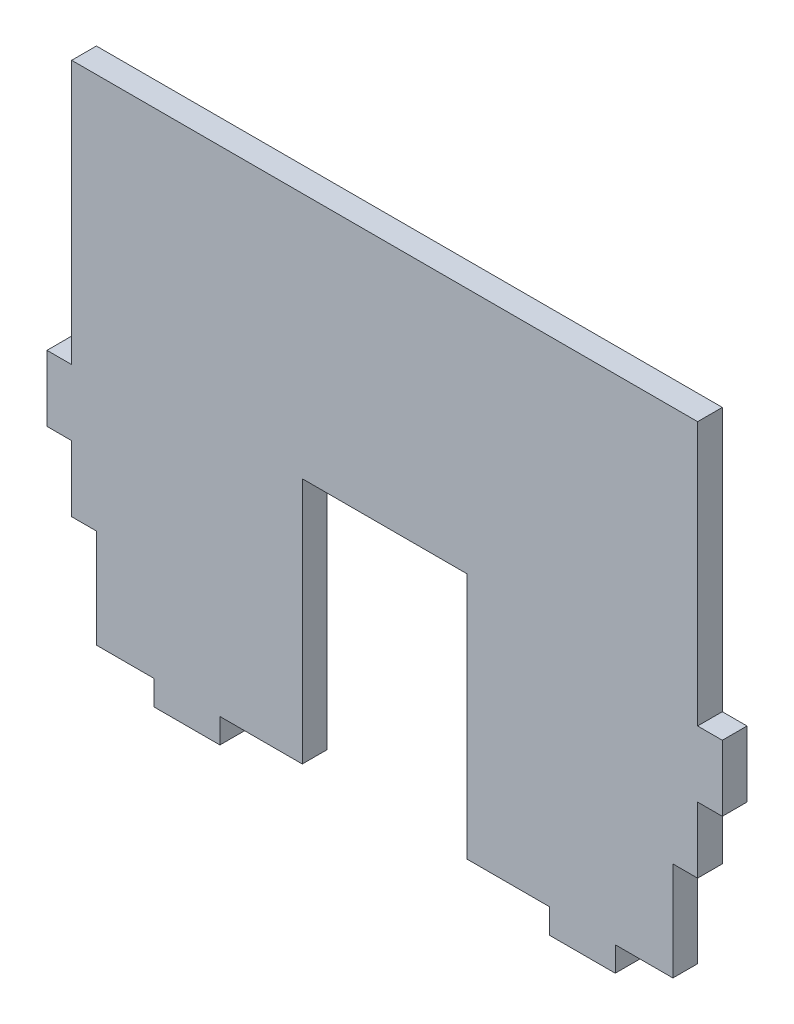
SolidWorks part; units mm, degrees
ref_plane "前视" through (0, 0, 0) normal (0, 0, 1) x (1, 0, 0)
ref_plane "上视" through (0, 0, 0) normal (0, 1, 0) x (1, 0, 0)
ref_plane "右视" through (0, 0, 0) normal (1, 0, 0) x (0, 0, -1)
sketch "草图1" plane through (0, 0, 0) normal (0, 0, 1) x (1, 0, 0)
  line L0 (10, 0) -> (10, -3)
  line L1 (3, 0) -> (10, 0)
  line L2 (0, 12) -> (0, 20)
  line L3 (0, 60) -> (76, 60)
  line L4 (0, 28) -> (-3, 28)
  line L5 (10, -3) -> (18, -3)
  line L6 (18, -3) -> (18, 0)
  line L7 (38, 80.2092) -> (38, -22.9169) construction
  line L8 (-3, 28) -> (-3, 20)
  line L9 (-3, 20) -> (0, 20)
  line L10 (28, 0) -> (28, 4.943)
  line L11 (28, 4.943) -> (28, 30)
  line L12 (28, 30) -> (48, 30)
  line L13 (0, 28) -> (0, 60)
  line L14 (18, 0) -> (28, 0)
  line L15 (58, 0) -> (48, 0)
  line L16 (76, 28) -> (76, 60)
  line L17 (48, 4.943) -> (48, 30)
  line L18 (48, 0) -> (48, 4.943)
  line L19 (79, 20) -> (76, 20)
  line L20 (79, 28) -> (79, 20)
  line L21 (58, -3) -> (58, 0)
  line L22 (66, -3) -> (58, -3)
  line L23 (76, 28) -> (79, 28)
  line L24 (76, 12) -> (76, 20)
  line L25 (73, 0) -> (66, 0)
  line L26 (66, 0) -> (66, -3)
  line L27 (0, 12) -> (3, 12)
  line L28 (3, 12) -> (3, 0)
  line L29 (73, 0) -> (73, 12)
  line L30 (73, 12) -> (76, 12)
  point P23 (38, 30)
  point P29 (38, 60)
  dimension "D2" = 3
  dimension "D3" = 38
  dimension "D4" = 8
  dimension "D5" = 10
  dimension "D6" = 30
  dimension "D7" = 10
  dimension "D8" = 8
  dimension "D9" = 20
  dimension "D10" = 3
  dimension "D11" = 3
  dimension "D12" = 12
  dimension "D13" = 3
  dimension "D14" = 12
extrude "凸台-拉伸1" add sketch "草图1" along normal blind 3
